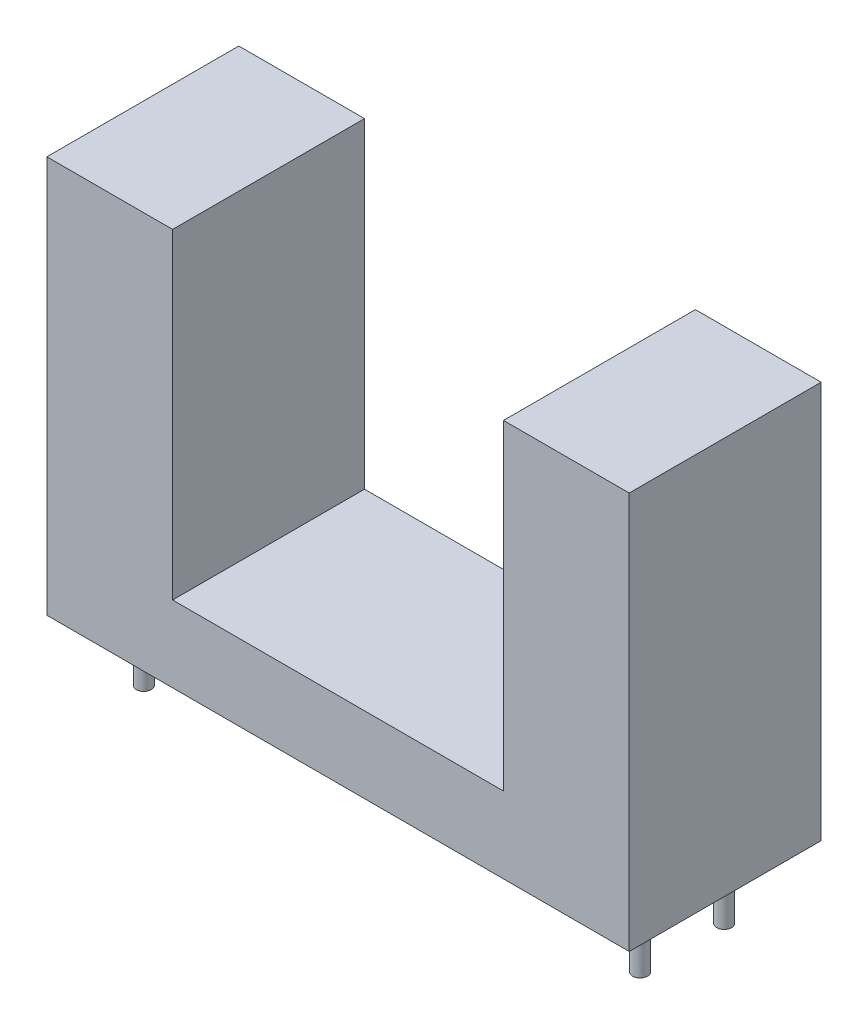
SolidWorks part; units mm, degrees
ref_plane "前视基准面" through (0, 0, 0) normal (0, 0, 1) x (1, 0, 0)
ref_plane "上视基准面" through (0, 0, 0) normal (0, 1, 0) x (1, 0, 0)
ref_plane "右视基准面" through (0, 0, 0) normal (1, 0, 0) x (0, 0, -1)
sketch "草图1" plane through (0, 0, 0) normal (0, 1, 0) x (1, 0, 0)
  line L1 (-8.8, 2.9) -> (8.8, 2.9)
  line L2 (-8.8, 2.9) -> (-8.8, -2.9)
  line L3 (-8.8, -2.9) -> (8.8, -2.9)
  line L4 (8.8, 2.9) -> (8.8, -2.9)
  point P4 (0, 2.9)
  point P6 (-8.8, 0)
  dimension "D1" = 5.8
  dimension "D2" = 17.6
extrude "凸台-拉伸1" add sketch "草图1" along normal blind 2.3
sketch "草图2" plane through (0, 2.3, 0) normal (0, 1, 0) x (1, 0, 0)
  line L0 (-8.8, -2.9) -> (8.8, -2.9) construction
  line L1 (-8.8, 2.9) -> (-5, 2.9)
  line L2 (-8.8, 2.9) -> (-8.8, -2.9)
  line L3 (-8.8, -2.9) -> (-5, -2.9)
  line L4 (-5, 2.9) -> (-5, -2.9)
  line L11 (8.8, 2.9) -> (5, 2.9)
  line L12 (8.8, 2.9) -> (8.8, -2.9)
  line L13 (8.8, -2.9) -> (5, -2.9)
  line L14 (5, 2.9) -> (5, -2.9)
  dimension "D1" = 3.8
  dimension "D2" = 3.8
extrude "凸台-拉伸2" add sketch "草图2" along normal blind 9.7
sketch "草图5" plane through (0, 0, 0) normal (0, -1, 0) x (1, 0, 0)
  circle A0 centre (-7.5, 1.27) radius 0.225
  circle A1 centre (-7.5, -1.27) radius 0.225
  circle A2 centre (7.5, 1.27) radius 0.225
  circle A3 centre (7.5, -1.27) radius 0.225
  dimension "D1" = 0.45
  dimension "D2" = 1.27
  dimension "D3" = 7.5
  dimension "D4" = 7.5
  dimension "D5" = 1.27
extrude "凸台-拉伸3" add sketch "草图5" along normal blind 2
